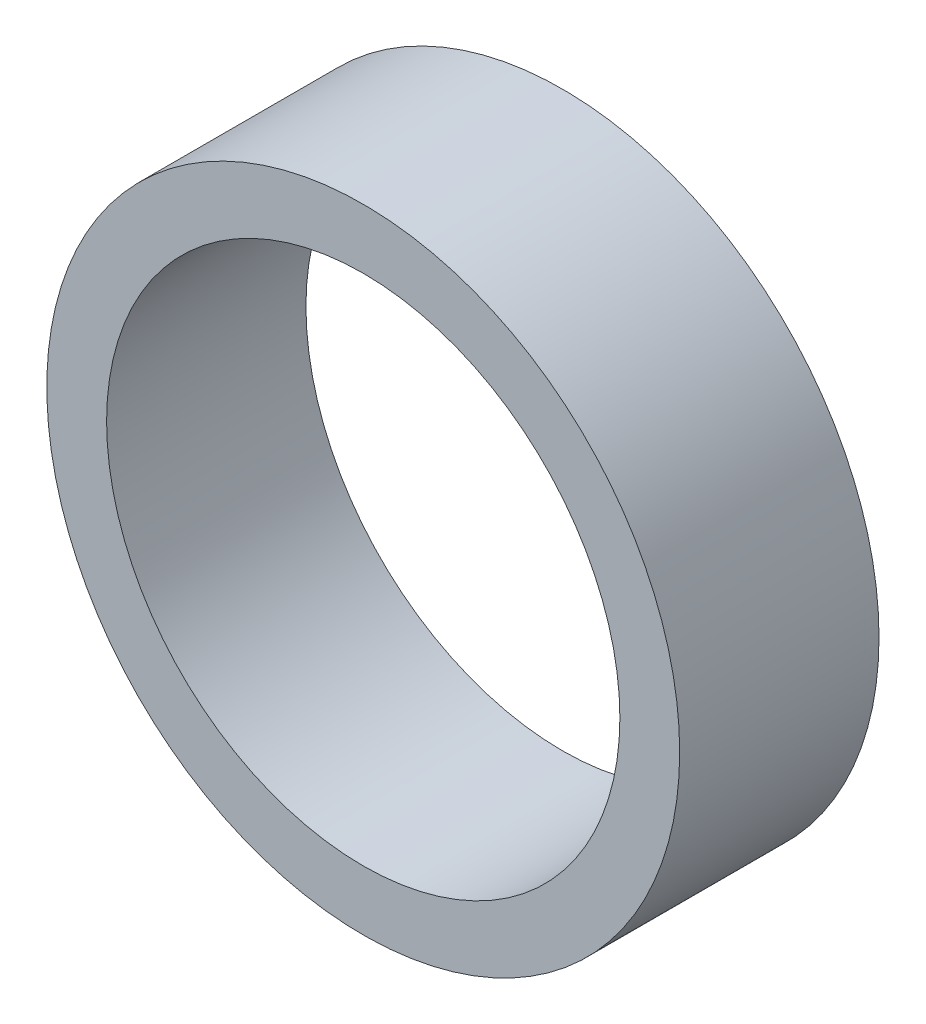
SolidWorks part; units mm, degrees
material "Tubo redondo com costura - 1/2\" x 1,2"
ref_plane "Plano frontal" through (0, 0, 0) normal (0, 0, 1) x (1, 0, 0)
ref_plane "Plano superior" through (0, 0, 0) normal (0, 1, 0) x (1, 0, 0)
ref_plane "Plano direito" through (0, 0, 0) normal (1, 0, 0) x (0, 0, -1)
sketch "Esboço1" plane through (0, 0, 0) normal (0, 0, 1) x (1, 0, 0)
  circle A0 centre (0, 0) radius 6.35
  circle A1 centre (0, 0) radius 5.15
  dimension "D1" = 12.7
  dimension "D2" = 1.2
extrude "Ressalto-extrusão1" add sketch "Esboço1" along normal blind 4
